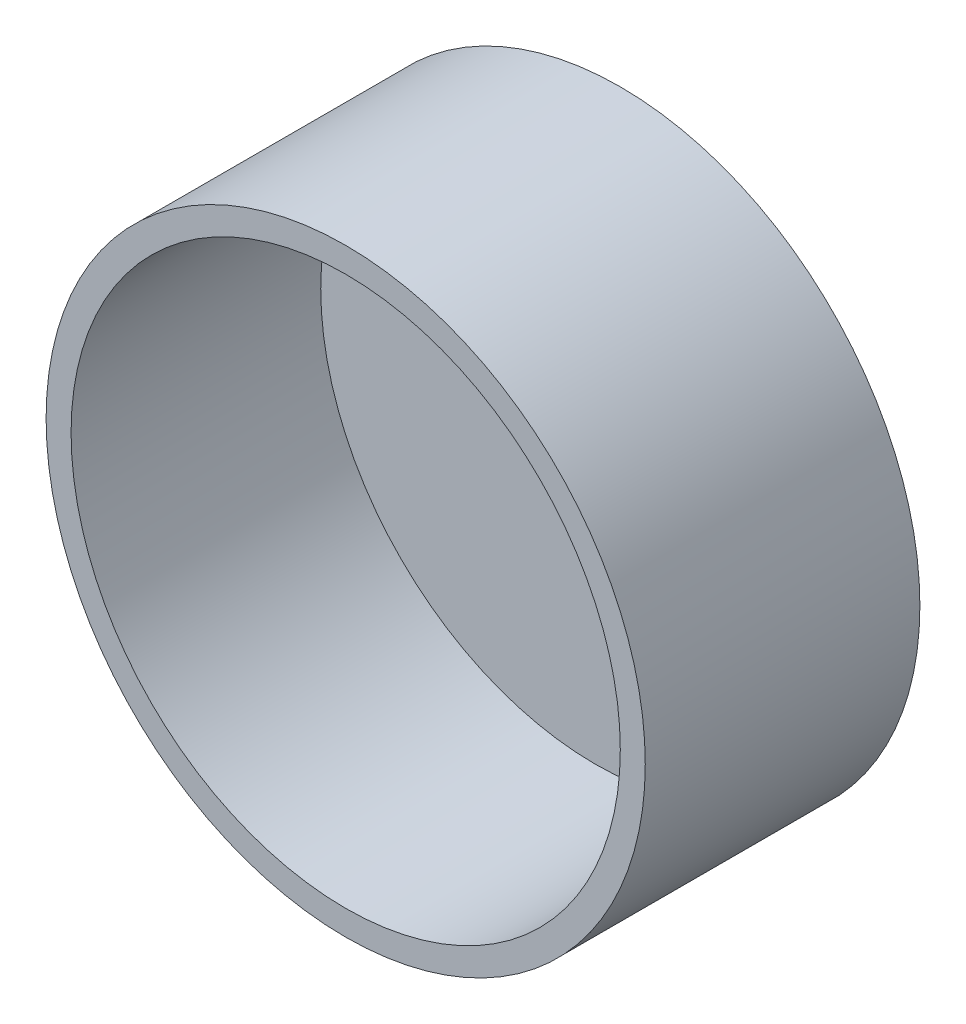
SolidWorks part; units mm, degrees
material "Rubber"
ref_plane "Front Plane" through (0, 0, 0) normal (0, 0, 1) x (1, 0, 0)
ref_plane "Top Plane" through (0, 0, 0) normal (0, 1, 0) x (1, 0, 0)
ref_plane "Right Plane" through (0, 0, 0) normal (1, 0, 0) x (0, 0, -1)
sketch "Sketch1" plane through (0, 0, 0) normal (0, 0, 1) x (1, 0, 0)
  circle A0 centre (0, 0) radius 27.94
  dimension "D1" = 55.88
extrude "Boss-Extrude1" add sketch "Sketch1" along normal blind 25.4
shell "Shell1" thickness 2.54
